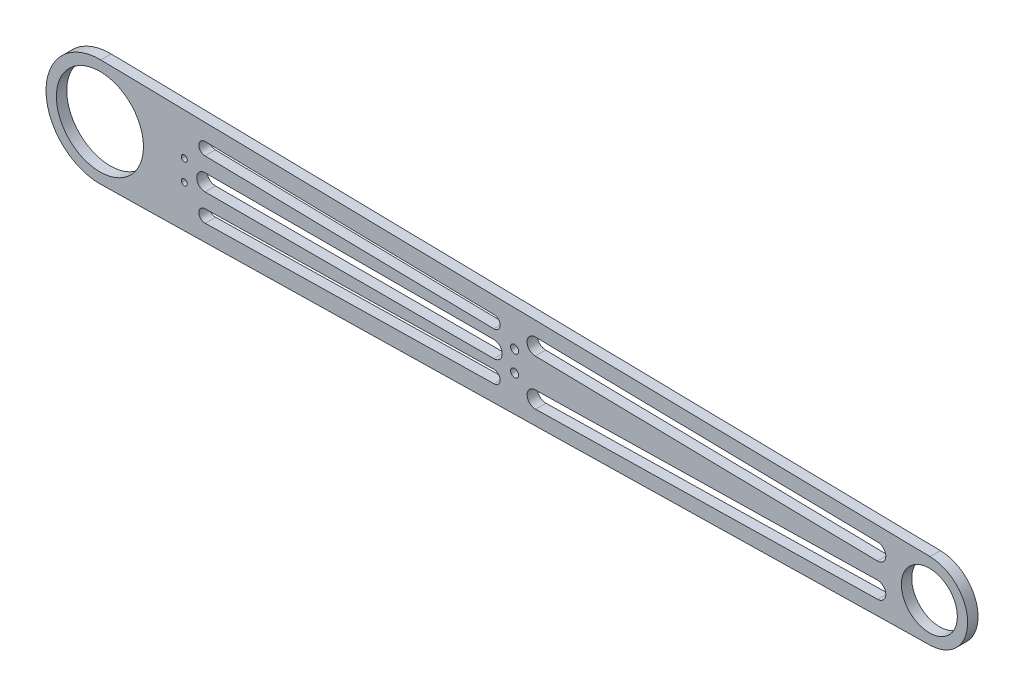
SolidWorks part; units mm, degrees
material "Thornel Mat VMA"
ref_plane "前视基准面" through (0, 0, 0) normal (0, 0, 1) x (1, 0, 0)
ref_plane "上视基准面" through (0, 0, 0) normal (0, 1, 0) x (1, 0, 0)
ref_plane "右视基准面" through (0, 0, 0) normal (1, 0, 0) x (0, 0, -1)
other "Configuration Table"
sketch "草图1" plane through (0, 0, 0) normal (0, 0, 1) x (1, 0, 0)
  line L0 (0, 0) -> (400, 0) construction
  line L3 (400.3469, 18.4967) -> (0.4875, 25.9954)
  line L4 (0.4875, -25.9954) -> (400.3469, -18.4967)
  arc A0 (0.4875, 25.9954) -> (0.4875, -25.9954) centre (0, 0) ccw
  arc A1 (400.3469, -18.4967) -> (400.3469, 18.4967) centre (400, 0) ccw
  circle A2 centre (0, 0) radius 21
  circle A3 centre (400, 0) radius 13.5
  point P3 (175, 0)
  dimension "D2" = 42
  dimension "D3" = 5
  dimension "D4" = 27
  dimension "D5" = 5
  dimension "D1" = 400
extrude "凸台-拉伸1" add sketch "草图1" along normal blind 5
sketch "草图2" plane through (0, 0, 5) normal (0, 0, 1) x (1, 0, 0)
  line L0 (400, 0) -> (0, 0) construction
  circle A0 centre (0, 0) radius 21 construction
  circle A1 centre (400, 0) radius 13.5 construction
sketch "草图4" plane through (0, 0, 0) normal (0, 0, -1) x (-1, 0, 0)
  line L0 (0, 0) -> (-40.694, -5) construction
  line L1 (0, 0) -> (-71.2051, 0) construction
  circle A0 centre (-40.694, -5) radius 1.45
  circle A1 centre (0, 0) radius 41 construction
  circle A2 centre (-40.694, 5) radius 1.45
  dimension "D2" = 2.9
  dimension "D1" = 82
  dimension "D3" = 10
extrude "切除-拉伸1" cut sketch "草图4" against normal through all
sketch "草图5" plane through (0, 0, 0) normal (0, 0, -1) x (-1, 0, 0)
  line L0 (-400, 0) -> (0, 0) construction
  line L1 (-200, 0) -> (-200, 47.5711) construction
  circle A0 centre (-200, 5) radius 1.95
  circle A1 centre (-200, -5) radius 1.95
  dimension "D1" = 5
  dimension "D2" = 3.9
extrude "切除-拉伸2" cut sketch "草图5" against normal through all
sketch "草图6" plane through (0, 0, 5) normal (0, 0, 1) x (1, 0, 0)
  line L0 (50.694, 14.052) -> (190, 11.4395) construction
  line L1 (50.7502, 17.0514) -> (190.0563, 14.439)
  line L2 (50.6377, 11.0525) -> (189.9438, 8.44)
  line L3 (400.3469, 18.4967) -> (0.4875, 25.9954) construction
  line L4 (210, 11.0644) -> (375, 7.9702) construction
  line L5 (210.075, 15.0637) -> (375.075, 11.9694)
  line L6 (209.925, 7.0651) -> (374.925, 3.9709)
  line L7 (0, 0) -> (400, 0) construction
  line L8 (210, -11.0644) -> (375, -7.9702) construction
  line L9 (210.075, -15.0637) -> (375.075, -11.9694)
  line L10 (209.925, -7.0651) -> (374.925, -3.9709)
  line L11 (50.694, -14.052) -> (190, -11.4395) construction
  line L12 (50.7502, -17.0514) -> (190.0563, -14.439)
  line L13 (50.6377, -11.0525) -> (189.9438, -8.44)
  line L14 (50.694, 0) -> (190, 0) construction
  line L15 (50.694, 4) -> (190, 4)
  line L16 (50.694, -4) -> (190, -4)
  arc A0 (50.7502, 17.0514) -> (50.6377, 11.0525) centre (50.694, 14.052) ccw
  arc A1 (189.9438, 8.44) -> (190.0563, 14.439) centre (190, 11.4395) ccw
  arc A2 (210.075, 15.0637) -> (209.925, 7.0651) centre (210, 11.0644) ccw
  arc A3 (374.925, 3.9709) -> (375.075, 11.9694) centre (375, 7.9702) ccw
  circle A4 centre (200, 5) radius 1.95 construction
  circle A5 centre (40.694, 5) radius 1.45 construction
  circle A6 centre (400, 0) radius 13.5 construction
  arc A7 (210.075, -15.0637) -> (209.925, -7.0651) centre (210, -11.0644) cw
  arc A8 (374.925, -3.9709) -> (375.075, -11.9694) centre (375, -7.9702) cw
  arc A9 (50.7502, -17.0514) -> (50.6377, -11.0525) centre (50.694, -14.052) cw
  arc A10 (189.9438, -8.44) -> (190.0563, -14.439) centre (190, -11.4395) cw
  arc A11 (50.694, 4) -> (50.694, -4) centre (50.694, 0) ccw
  arc A12 (190, -4) -> (190, 4) centre (190, 0) ccw
  point P2 (120.347, 12.7457)
  point P12 (292.5, 9.5173)
  point P18 (292.5, -9.5173)
  point P35 (120.347, -12.7457)
  point P42 (120.347, 0)
  dimension "D5" = 10
  dimension "D6" = 10
  dimension "D7" = 10
  dimension "D8" = 25
  dimension "D1" = 6
  dimension "D2" = 8
  dimension "D3" = 8
  dimension "D4" = 7
  dimension "D9" = 8
extrude "切除-拉伸3" cut sketch "草图6" against normal through all
